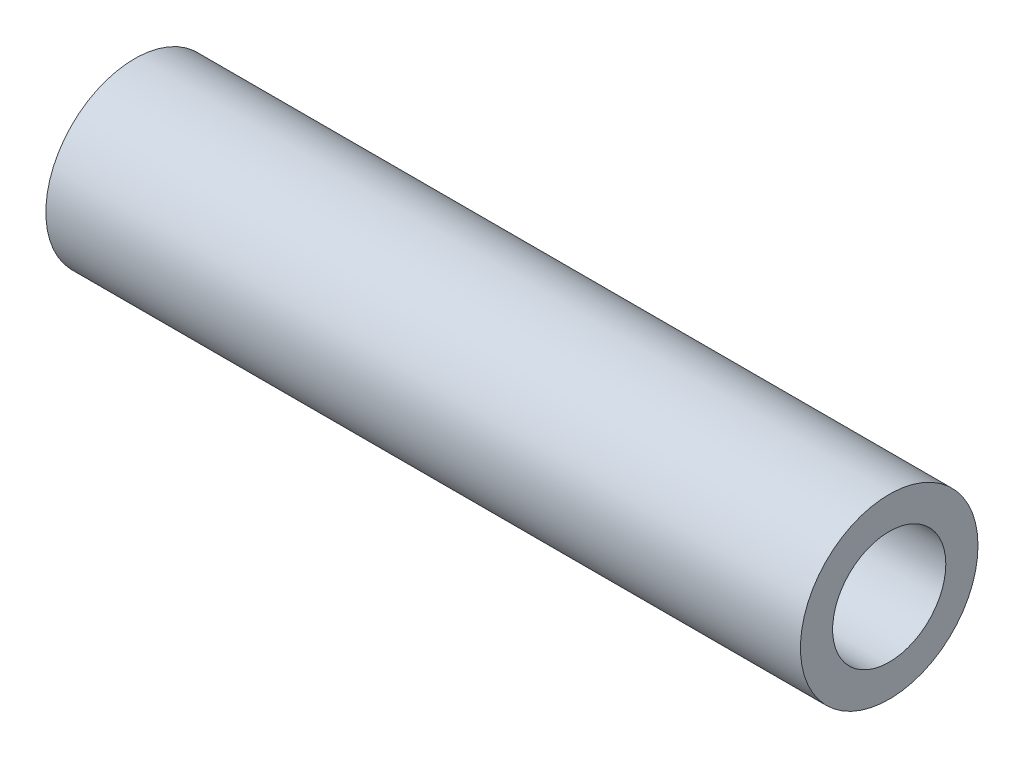
SolidWorks part; units mm, degrees
material "Delrin 2700 NC010, Low Viscosity Acetal Copolymer (SS)"
ref_plane "Front Plane" through (0, 0, 0) normal (0, 0, 1) x (1, 0, 0)
ref_plane "Top Plane" through (0, 0, 0) normal (0, 1, 0) x (1, 0, 0)
ref_plane "Right Plane" through (0, 0, 0) normal (1, 0, 0) x (0, 0, -1)
sketch "Sketch1" plane through (0, 0, 0) normal (1, 0, 0) x (0, 0, -1)
  circle A0 centre (0, 0) radius 4
  circle A1 centre (0, 0) radius 2.55
  dimension "D1" = 8
  dimension "D2" = 5.1
extrude "Boss-Extrude1" add sketch "Sketch1" along normal blind 34
